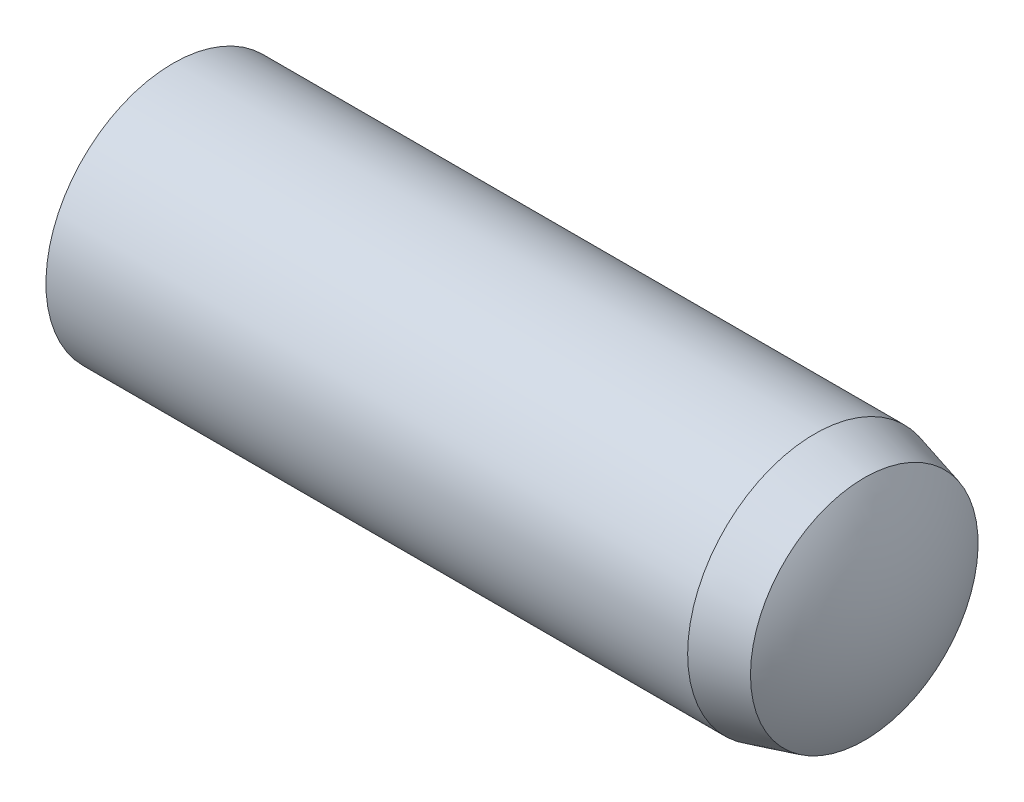
SolidWorks part; units mm, degrees
material "AISI 1020"
ref_plane "Front Plane" through (0, 0, 0) normal (0, 0, 1) x (1, 0, 0)
ref_plane "Top Plane" through (0, 0, 0) normal (0, 1, 0) x (1, 0, 0)
ref_plane "Right Plane" through (0, 0, 0) normal (1, 0, 0) x (0, 0, -1)
sketch "Sketch1" plane through (0, 0, 0) normal (0, 0, 1) x (1, 0, 0)
  line L0 (-12, 0) -> (12, 0) construction
  line L1 (12, 4) -> (12, -4) construction
  line L2 (-12, 4) -> (-12, -4) construction
  line L3 (9.4, 4) -> (9.4, -4) construction
  line L4 (-10.8, 4) -> (-10.8, -4) construction
  line L5 (-12, 0) -> (-10.8, 0) construction
  line L6 (12, 0) -> (9.4, 0) construction
  line L7 (10.96, 4) -> (10.96, -4) construction
  dimension "Dia" = 8
  dimension "Length" = 24
  dimension "D1" = 2.6
  dimension "D2" = 1.2
  dimension "D3" = 1.56
sketch "Sketch2" plane through (0, 0, 0) normal (1, 0, 0) x (0, 0, -1)
  circle A0 centre (0, 0) radius 4
extrude "Extrude1" add sketch "Sketch2" against normal up to vertex (12 mm away) and the other way up to vertex (12 mm away) up to point (-12, 0, 0) other way up to point (12, 0, 0)
sketch "Sketch5" plane through (0, 0, 0) normal (0, 0, 1) x (1, 0, 0)
  line L0 (9.4, 4) -> (9.4, 4.5)
  line L1 (9.4, 4.5) -> (12.5, 4.5)
  line L2 (12.5, 4.5) -> (12.5, 0)
  line L3 (12, 0) -> (12.5, 0)
  line L5 (-10.8, 4) -> (-10.8, 4.5)
  line L6 (-10.8, 4.5) -> (-12.5, 4.5)
  line L7 (-12.5, 4.5) -> (-12.5, 0)
  line L8 (9.4, 4) -> (10.96, 3.582)
  line L10 (-12, 0) -> (-12.5, 0)
  line L11 (-12, 4) -> (-12, -4) construction
  line L13 (9.4, 4) -> (9.4, -4) construction
  line L15 (-12, 0) -> (12, 0) construction
  line L16 (10.96, 4) -> (10.96, -4) construction
  line L17 (12, 4) -> (12, -4) construction
  arc A0 (10.96, 3.582) -> (12, 0) centre (5.3114, 0) cw
  arc A1 (-10.8, 4) -> (-12, 0) centre (-4.7333, 0) ccw
  dimension "D1" = 15
  dimension "D2" = 0.5
revolve "Cut-Revolve1" cut sketch "Sketch5" angle 360 about L0
ref_plane "Plane1" through (12, 0, 0) normal (1, 0, 0) x (0, 0, -1)
equation "\"D1@Sketch1\" = \"Dia@Sketch1\"*.325"
equation "\"D2@Sketch1\" = \"Dia@Sketch1\"*.15"
equation "\"D3@Sketch1\" = \"D1@Sketch1\"*.6"
